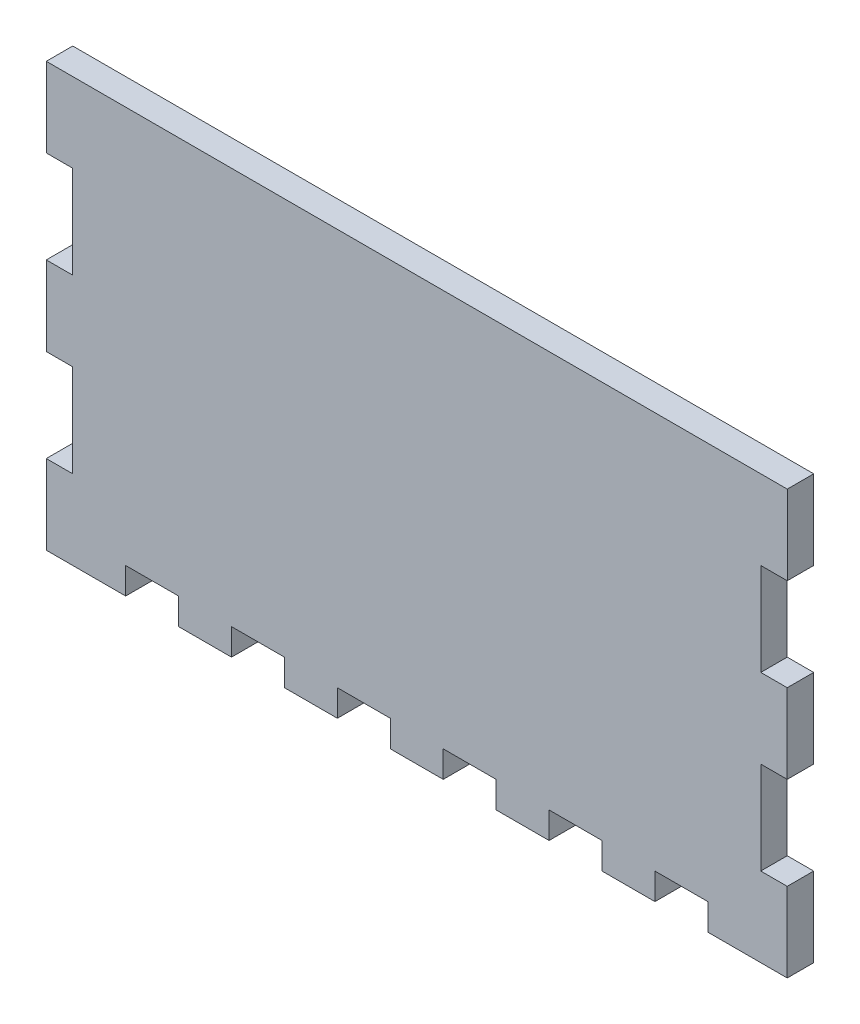
SolidWorks part; units mm, degrees
ref_plane "Front Plane" through (0, 0, 0) normal (0, 0, 1) x (1, 0, 0)
ref_plane "Top Plane" through (0, 0, 0) normal (0, 1, 0) x (1, 0, 0)
ref_plane "Right Plane" through (0, 0, 0) normal (1, 0, 0) x (0, 0, -1)
sketch "Sketch1" plane through (0, 0, 0) normal (0, 0, 1) x (1, 0, 0)
  line L0 (69.0386, -4.6833) -> (64.0386, -4.6833)
  line L1 (-55.9553, -32.1833) -> (-45.9553, -32.1833)
  line L2 (44.0447, -32.1833) -> (54.0447, -32.1833)
  line L3 (-35.9553, -32.1833) -> (-25.9553, -32.1833)
  line L4 (4.0447, -32.1833) -> (14.0447, -32.1833)
  line L5 (-65.9553, 27.8167) -> (-65.9553, 10.3167)
  line L6 (-65.9553, -4.6833) -> (-65.9553, -22.1833)
  line L7 (-70.9553, 42.8167) -> (69.0447, 42.8167)
  line L8 (-45.9553, -37.1833) -> (-35.9553, -37.1833)
  line L9 (-70.9553, -37.1833) -> (-55.9553, -37.1833)
  line L10 (69.0447, 42.8167) -> (69.0447, 27.8167)
  line L11 (64.0386, -4.6833) -> (64.0386, -22.1833)
  line L14 (69.0386, -37.1833) -> (69.0386, -22.1833)
  line L15 (69.0386, -22.1833) -> (64.0386, -22.1833)
  line L16 (-70.9553, -37.1833) -> (-55.9553, -37.1833)
  line L17 (69.0386, -4.6833) -> (69.0386, 10.3167)
  line L18 (69.0386, 10.3167) -> (64.0386, 10.3167)
  line L20 (-65.9553, -4.6833) -> (-70.9553, -4.6833)
  line L21 (69.0386, -37.1833) -> (54.0447, -37.1833)
  line L23 (-55.9553, -37.1833) -> (-55.9553, -32.1833)
  line L24 (-65.9553, 27.8167) -> (-70.9553, 27.8167)
  line L25 (-70.9553, 42.8167) -> (-70.9553, 27.8167)
  line L28 (-65.9553, -22.1833) -> (-70.9553, -22.1833)
  line L29 (-70.9553, -37.1833) -> (-70.9553, -22.1833)
  line L30 (-45.9553, -37.1833) -> (-45.9553, -32.1833)
  line L31 (-65.9553, 10.3167) -> (-70.9553, 10.3167)
  line L32 (-70.9553, -4.6833) -> (-70.9553, 10.3167)
  line L34 (-70.9553, 27.8167) -> (-65.9553, 27.8167)
  line L36 (-70.9553, 10.3167) -> (-65.9553, 10.3167)
  line L37 (-65.9553, 27.8167) -> (-65.9553, 10.3167)
  line L38 (-70.9553, -4.6833) -> (-65.9553, -4.6833)
  line L40 (-70.9553, -22.1833) -> (-65.9553, -22.1833)
  line L41 (-65.9553, -4.6833) -> (-65.9553, -22.1833)
  line L42 (64.0386, -4.6833) -> (69.0386, -4.6833)
  line L43 (64.0386, -4.6833) -> (64.0386, -22.1833)
  line L44 (64.0386, -22.1833) -> (69.0386, -22.1833)
  line L46 (64.0386, 27.8167) -> (69.0447, 27.8167)
  line L47 (64.0386, 27.8167) -> (64.0386, 10.3167)
  line L48 (64.0386, 10.3167) -> (69.0386, 10.3167)
  line L50 (-15.9553, -37.1833) -> (-15.9553, -32.1833)
  line L51 (-25.9553, -37.1833) -> (-15.9553, -37.1833)
  line L52 (-45.9553, -32.1833) -> (-45.9553, -37.1833)
  line L55 (-35.9553, -37.1833) -> (-35.9553, -32.1833)
  line L60 (-15.9553, -37.1833) -> (-15.9553, -32.1833)
  line L61 (-25.9553, -37.1833) -> (-25.9553, -32.1833)
  line L62 (-15.9553, -32.1833) -> (-5.9553, -32.1833)
  line L64 (-5.9553, -37.1833) -> (4.0447, -37.1833)
  line L65 (-15.9553, -37.1833) -> (-15.9553, -32.1833)
  line L67 (-15.9553, -37.1833) -> (-15.9553, -32.1833)
  line L82 (-5.9553, -37.1833) -> (-5.9553, -32.1833)
  line L90 (14.0447, -37.1833) -> (24.0447, -37.1833)
  line L93 (4.0447, -37.1833) -> (4.0447, -32.1833)
  line L99 (14.0447, -37.1833) -> (14.0447, -32.1833)
  line L100 (24.0447, -32.1833) -> (34.0447, -32.1833)
  line L102 (34.0447, -37.1833) -> (44.0447, -37.1833)
  line L104 (34.0447, -37.1833) -> (34.0447, -32.1833)
  line L105 (24.0447, -37.1833) -> (24.0447, -32.1833)
  line L109 (34.0447, -37.1833) -> (34.0447, -32.1833)
  line L111 (34.0447, -37.1833) -> (34.0447, -32.1833)
  line L116 (54.0447, -37.1833) -> (54.0447, -32.1833)
  line L117 (44.0447, -37.1833) -> (44.0447, -32.1833)
  dimension "D1" = 10
  dimension "D3" = 140
  dimension "D4" = 80
extrude "Boss-Extrude1" add sketch "Sketch1" along normal blind 5
